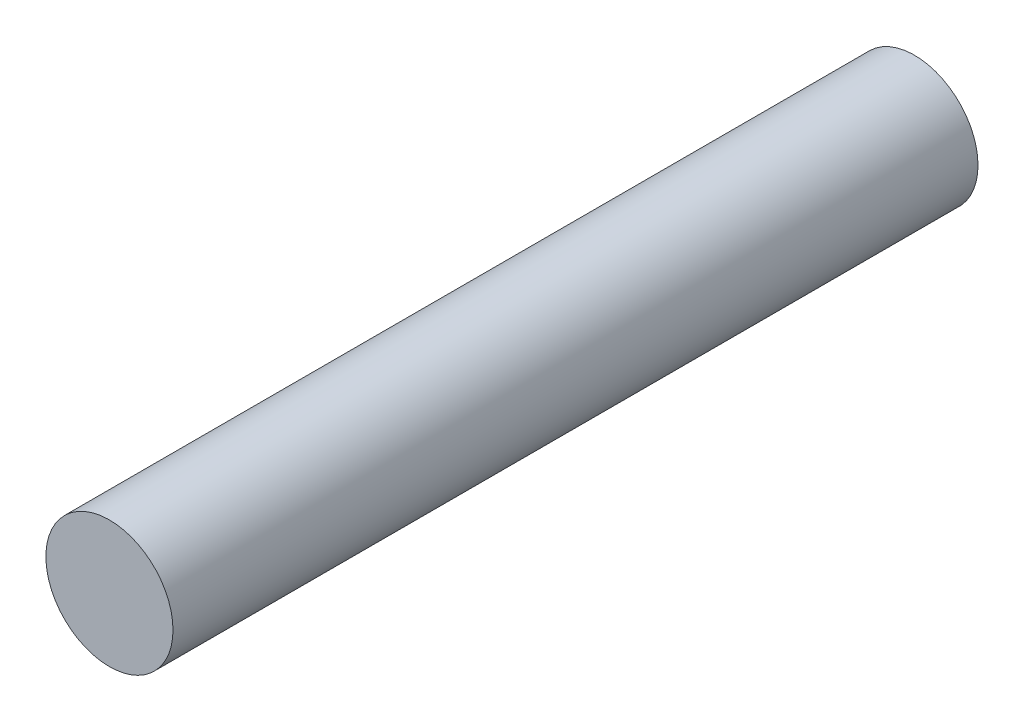
SolidWorks part; units mm, degrees
ref_plane "Front Plane" through (0, 0, 0) normal (0, 0, 1) x (1, 0, 0)
ref_plane "Top Plane" through (0, 0, 0) normal (0, 1, 0) x (1, 0, 0)
ref_plane "Right Plane" through (0, 0, 0) normal (1, 0, 0) x (0, 0, -1)
sketch "Sketch1" plane through (0, 0, 0) normal (0, 0, 1) x (1, 0, 0)
  circle A0 centre (0, 0) radius 30
extrude "Boss-Extrude1" add sketch "Sketch1" along normal blind 380
